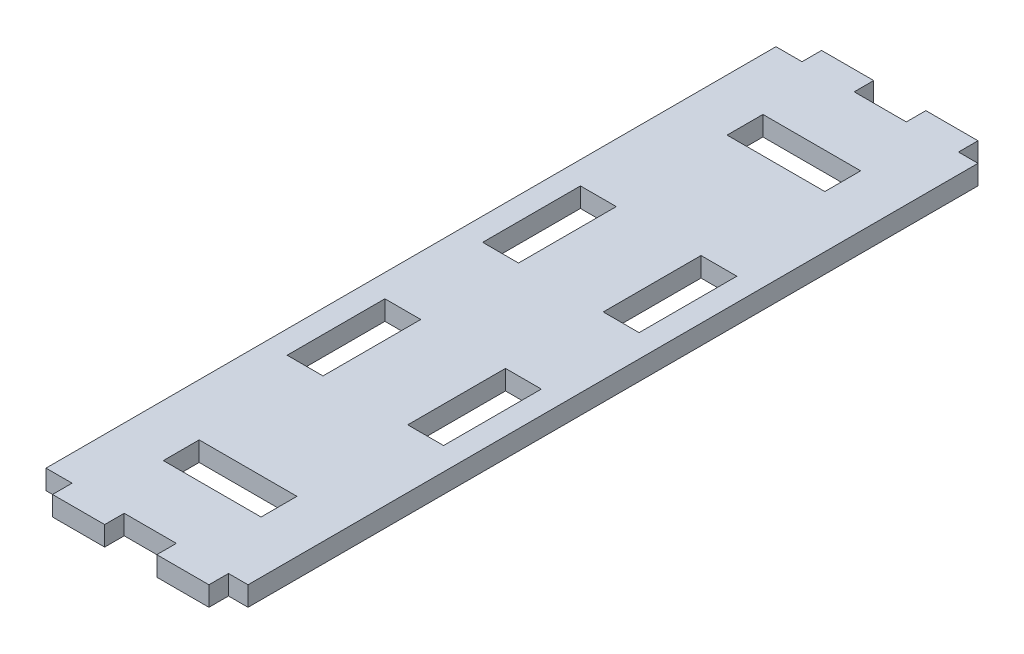
SolidWorks part; units mm, degrees
ref_plane "Front Plane" through (0, 0, 0) normal (0, 0, 1) x (1, 0, 0)
ref_plane "Top Plane" through (0, 0, 0) normal (0, 1, 0) x (1, 0, 0)
ref_plane "Right Plane" through (0, 0, 0) normal (1, 0, 0) x (0, 0, -1)
sketch "Sketch1" plane through (0, 0, 0) normal (0, 1, 0) x (1, 0, 0)
  line L0 (0, 56) -> (0, -56)
  line L1 (0, -56) -> (-3, -56)
  line L2 (-3, -56) -> (-3, -59)
  line L3 (-3, -59) -> (-11, -59)
  line L4 (-11, -59) -> (-11, -56)
  line L5 (-11, -56) -> (-19, -56)
  line L6 (-19, -56) -> (-19, -59)
  line L7 (-19, -59) -> (-27, -59)
  line L8 (-27, -59) -> (-27, -56)
  line L9 (-27, -56) -> (-31, -56)
  line L10 (-31, -56) -> (-31, 56)
  line L11 (-31, 0) -> (0, 0) construction
  line L12 (-27, 56) -> (-31, 56)
  line L13 (-27, 59) -> (-27, 56)
  line L14 (-19, 59) -> (-27, 59)
  line L15 (-19, 56) -> (-19, 59)
  line L16 (-11, 56) -> (-19, 56)
  line L17 (-11, 59) -> (-11, 56)
  line L18 (-3, 59) -> (-11, 59)
  line L19 (-3, 56) -> (-3, 59)
  line L20 (0, 56) -> (-3, 56)
  line L21 (-15.5, 0) -> (-15.5, -40.5) construction
  line L22 (-23, -46) -> (-23, -40.5)
  line L23 (-23, -46) -> (-8, -46)
  line L24 (-27.5, -7.5) -> (-27.5, -22.5)
  line L25 (-23, -40.5) -> (-8, -40.5)
  line L26 (-8, -46) -> (-8, -40.5)
  line L27 (-9, -7.5) -> (-3.5, -7.5)
  line L28 (-9, -7.5) -> (-9, -22.5)
  line L29 (-9, -22.5) -> (-3.5, -22.5)
  line L30 (-3.5, -7.5) -> (-3.5, -22.5)
  line L31 (-22, -22.5) -> (-27.5, -22.5)
  line L32 (-22, -7.5) -> (-22, -22.5)
  line L33 (-22, -7.5) -> (-27.5, -7.5)
  line L34 (-22, 7.5) -> (-27.5, 7.5)
  line L35 (-22, 7.5) -> (-22, 22.5)
  line L36 (-22, 22.5) -> (-27.5, 22.5)
  line L37 (-3.5, 7.5) -> (-3.5, 22.5)
  line L38 (-9, 22.5) -> (-3.5, 22.5)
  line L39 (-9, 7.5) -> (-9, 22.5)
  line L40 (-9, 7.5) -> (-3.5, 7.5)
  line L41 (-8, 46) -> (-8, 40.5)
  line L42 (-23, 40.5) -> (-8, 40.5)
  line L43 (-27.5, 7.5) -> (-27.5, 22.5)
  line L44 (-23, 46) -> (-8, 46)
  line L45 (-23, 46) -> (-23, 40.5)
  point P34 (-15.5, -46)
  point P50 (-15.5, 46)
  dimension "D1" = 56
  dimension "D2" = 8
  dimension "D3" = 8
  dimension "D4" = 8
  dimension "D5" = 4
  dimension "D6" = 3
  dimension "D7" = 3
  dimension "D8" = 7.5
  dimension "D9" = 5.5
  dimension "D10" = 46
  dimension "D11" = 5.5
  dimension "D12" = 6.5
  dimension "D13" = 7.5
  dimension "D14" = 15
extrude "Boss-Extrude1" add sketch "Sketch1" along normal blind 3
